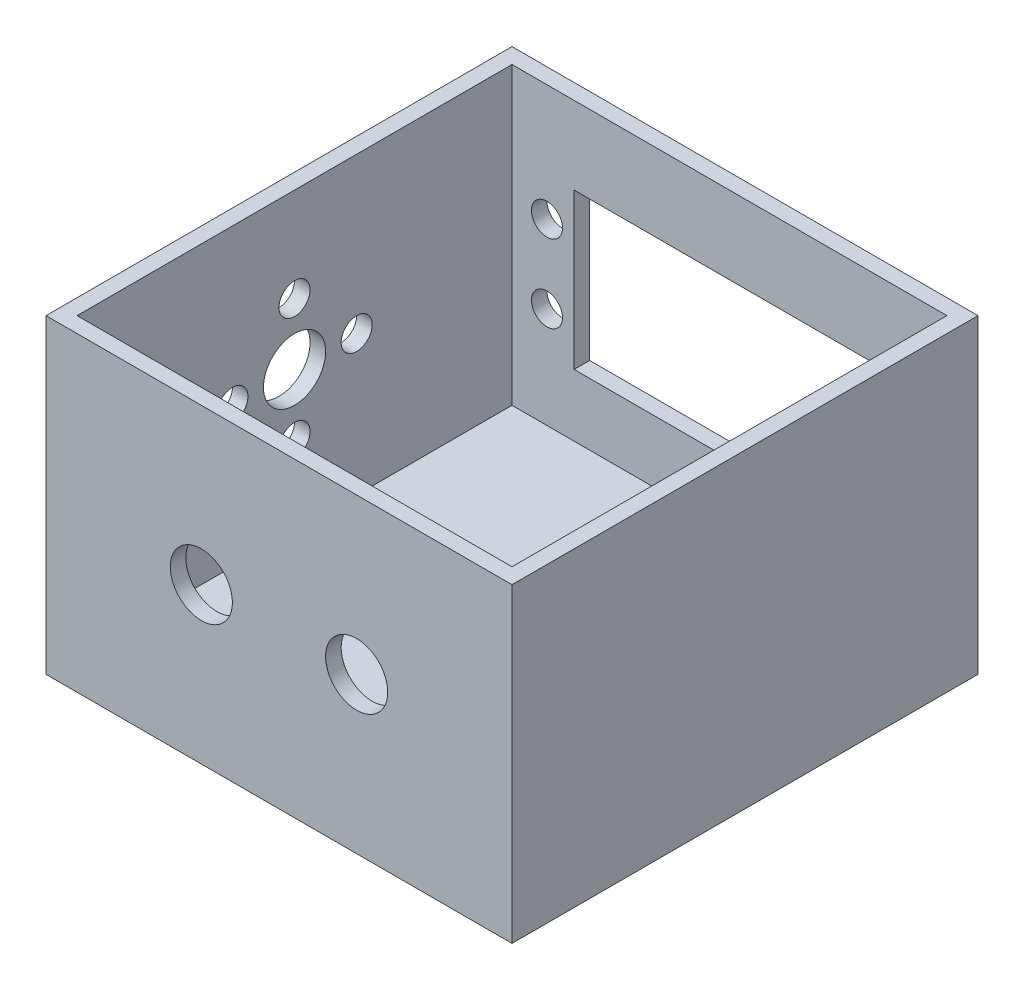
SolidWorks part; units mm, degrees
ref_plane "Ön Düzlem" through (0, 0, 0) normal (0, 0, 1) x (1, 0, 0)
ref_plane "Üst Düzlem" through (0, 0, 0) normal (0, 1, 0) x (1, 0, 0)
ref_plane "Sağ Düzlem" through (0, 0, 0) normal (1, 0, 0) x (0, 0, -1)
sketch "Çizim2" plane through (0, 0, 0) normal (0, 0, 1) x (1, 0, 0)
  line L1 (0, 0) -> (60, 0)
  line L2 (0, 0) -> (0, 40)
  line L3 (0, 40) -> (60, 40)
  line L4 (60, 0) -> (60, 40)
  dimension "D1" = 40
  dimension "D2" = 60
extrude "Yükseklik-Ekstrüzyon1" add sketch "Çizim2" along normal blind 60
shell "İç Boşaltma1" thickness 2
sketch "Çizim4" plane through (0, 0, 0) normal (0, 0, -1) x (-1, 0, 0)
  line L0 (-60, 0) -> (-60, 40) construction
  line L1 (-50, 30) -> (-10, 30)
  line L2 (-50, 30) -> (-50, 10)
  line L3 (-50, 10) -> (-10, 10)
  line L4 (-10, 30) -> (-10, 10)
  line L5 (0, 0) -> (-60, 0) construction
  circle A0 centre (-53.5, 25) radius 2
  circle A1 centre (-53.5, 15) radius 2
  circle A2 centre (-6.5, 15) radius 2
  circle A3 centre (-6.5, 25) radius 2
  dimension "D7" = 4
  dimension "D5" = 4
  dimension "D1" = 40
  dimension "D2" = 20
  dimension "D3" = 10
  dimension "D4" = 10
extrude "Kes-Ekstrüzyon2" cut sketch "Çizim4" against normal up to next
sketch "Çizim5" plane through (0, 0, 0) normal (0, -1, 0) x (1, 0, 0)
  circle A0 centre (30, 30) radius 2
  circle A1 centre (38, 30) radius 2
  circle A2 centre (38, 38) radius 2 [skipped]
  circle A3 centre (30, 38) radius 2
  circle A4 centre (30, 22) radius 2
  circle A5 centre (22, 30) radius 2
  dimension "D1" = 4
  dimension "D4" = 8
  dimension "D5" = 8
  dimension "D2" = 2
  dimension "D3" = 2
extrude "Kes-Ekstrüzyon3" cut sketch "Çizim5" against normal up to next
sketch "Çizim6" plane through (0, 0, 60) normal (0, 0, 1) x (1, 0, 0)
  line L0 (0, 40) -> (0, 0) construction
  line L1 (60, 40) -> (0, 40) construction
  line L2 (30, 40) -> (30, 0) construction
  line L4 (0, 0) -> (60, 0) construction
  circle A0 centre (20, 20) radius 4
  circle A1 centre (40, 20) radius 4
  dimension "D2" = 8
  dimension "D1" = 20
  dimension "D3" = 20
extrude "Kes-Ekstrüzyon4" cut sketch "Çizim6" against normal up to next contours A0 | A1
sketch "Çizim7" plane through (0, 0, 0) normal (-1, 0, 0) x (0, 0, 1)
  circle A0 centre (30, 20) radius 4
  circle A1 centre (22, 20) radius 2
  circle A2 centre (38, 20) radius 2
  circle A3 centre (30, 27.8983) radius 2
  circle A4 centre (30, 12.1017) radius 2
  dimension "D1" = 8
  dimension "D2" = 4
  dimension "D3" = 8
  dimension "D4" = 4
extrude "Kes-Ekstrüzyon5" cut sketch "Çizim7" against normal up to next
